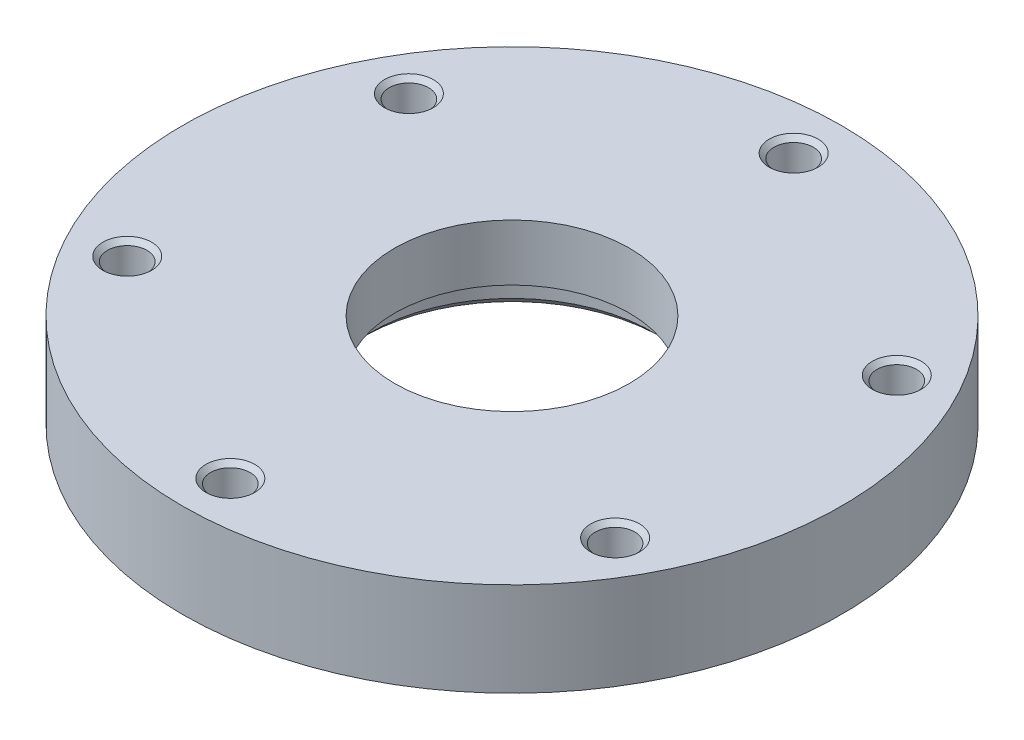
SolidWorks part; units mm, degrees
ref_plane "Front Plane" through (0, 0, 0) normal (0, 0, 1) x (1, 0, 0)
ref_plane "Top Plane" through (0, 0, 0) normal (0, 1, 0) x (1, 0, 0)
ref_plane "Right Plane" through (0, 0, 0) normal (1, 0, 0) x (0, 0, -1)
sketch "Sketch1" plane through (0, 0, 0) normal (0, 1, 0) x (1, 0, 0)
  circle A0 centre (0, 0) radius 35.1
  circle A1 centre (0, 0) radius 30 construction
  circle A2 centre (0, 30) radius 2.1
  circle A3 centre (25.9808, 15) radius 2.1
  circle A4 centre (25.9808, -15) radius 2.1
  circle A5 centre (0, -30) radius 2.1
  circle A6 centre (-25.9808, -15) radius 2.1
  circle A7 centre (-25.9808, 15) radius 2.1
  circle A8 centre (0, 0) radius 15
  dimension "D1" = 60
  dimension "D2" = 70.2
  dimension "D3" = 4.2
  dimension "D5" = 30
  dimension "D4" = 6
extrude "Main Body" add sketch "Sketch1" along normal blind 10
chamfer "Chamfer3" distance 0.5 angle 45 6 edges at (-25.9808, 10, -12.9) (-25.9808, 10, 17.1) (0, 10, 32.1) (25.9808, 10, 17.1) (25.9808, 10, -12.9) (0, 10, -27.9)
chamfer "Chamfer4" distance 1 angle 45 1 edges at (0, 0, 15)
sketch "Sketch2" plane through (0, 10, 0) normal (0, 1, 0) x (1, 0, 0)
  circle A0 centre (0, 0) radius 15
  circle A1 centre (0, 0) radius 12.5
  circle A2 centre (0, 0) radius 15 construction
  dimension "D1" = 2.5
extrude "Boss-Extrude4" add sketch "Sketch2" against normal blind 6
sketch "Sketch3" plane through (0, 0, 0) normal (0, -1, 0) x (1, 0, 0)
  line L0 (25.9808, 10.9585) -> (29.4808, 12.9793)
  line L1 (0, 25.9585) -> (3.5, 27.9793)
  line L2 (3.5, 27.9793) -> (3.5, 32.0207)
  line L3 (3.5, 32.0207) -> (0, 34.0415)
  line L4 (0, 34.0415) -> (-3.5, 32.0207)
  line L5 (-3.5, 32.0207) -> (-3.5, 27.9793)
  line L6 (-3.5, 27.9793) -> (0, 25.9585)
  line L7 (29.4808, 12.9793) -> (29.4808, 17.0207)
  line L8 (29.4808, 17.0207) -> (25.9808, 19.0415)
  line L9 (25.9808, 19.0415) -> (22.4808, 17.0207)
  line L10 (22.4808, 17.0207) -> (22.4808, 12.9793)
  line L11 (22.4808, 12.9793) -> (25.9808, 10.9585)
  line L12 (22.4808, -17.0207) -> (25.9808, -19.0415)
  line L13 (25.9808, -19.0415) -> (29.4808, -17.0207)
  line L14 (29.4808, -17.0207) -> (29.4808, -12.9793)
  line L15 (29.4808, -12.9793) -> (25.9808, -10.9585)
  line L16 (25.9808, -10.9585) -> (22.4808, -12.9793)
  line L17 (22.4808, -12.9793) -> (22.4808, -17.0207)
  line L18 (-3.5, -27.9793) -> (-3.5, -32.0207)
  line L19 (-3.5, -32.0207) -> (0, -34.0415)
  line L20 (0, -34.0415) -> (3.5, -32.0207)
  line L21 (3.5, -32.0207) -> (3.5, -27.9793)
  line L22 (3.5, -27.9793) -> (0, -25.9585)
  line L23 (0, -25.9585) -> (-3.5, -27.9793)
  line L24 (-25.9808, -10.9585) -> (-29.4808, -12.9793)
  line L25 (-29.4808, -12.9793) -> (-29.4808, -17.0207)
  line L26 (-29.4808, -17.0207) -> (-25.9808, -19.0415)
  line L27 (-25.9808, -19.0415) -> (-22.4808, -17.0207)
  line L28 (-22.4808, -17.0207) -> (-22.4808, -12.9793)
  line L29 (-22.4808, -12.9793) -> (-25.9808, -10.9585)
  line L30 (-22.4808, 17.0207) -> (-25.9808, 19.0415)
  line L31 (-25.9808, 19.0415) -> (-29.4808, 17.0207)
  line L32 (-29.4808, 17.0207) -> (-29.4808, 12.9793)
  line L33 (-29.4808, 12.9793) -> (-25.9808, 10.9585)
  line L34 (-25.9808, 10.9585) -> (-22.4808, 12.9793)
  line L35 (-22.4808, 12.9793) -> (-22.4808, 17.0207)
  circle A0 centre (0, 30) radius 3.5 construction
  point P41 (0, 0)
  dimension "D2" = 6
  dimension "D1" = 7
extrude "Cut-Extrude1" cut sketch "Sketch3" against normal blind 2.5
equation "\"pattern_line\"= 60"
equation "\"shaft_diamter\"= 4.2"
equation "\"bearing_OD\"= 30"
equation "\"OD\"=70.2"
equation "\"D1@Sketch1\"=\"pattern_line\""
equation "\"D2@Sketch1\"=\"OD\""
equation "\"D3@Sketch1\"=\"shaft_diamter\""
equation "\"D5@Sketch1\"=\"bearing_OD\""
